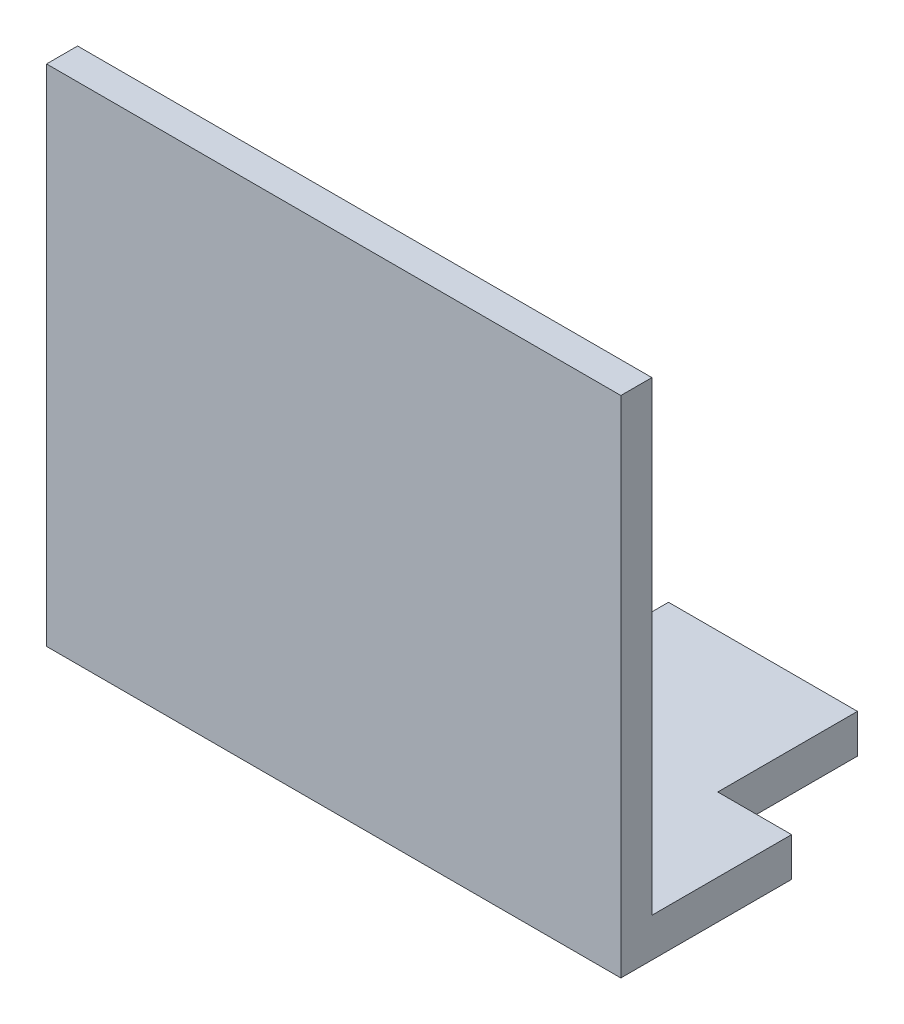
SolidWorks part; units mm, degrees
ref_plane "Спереди" through (0, 0, 0) normal (0, 0, 1) x (1, 0, 0)
ref_plane "Сверху" through (0, 0, 0) normal (0, 1, 0) x (1, 0, 0)
ref_plane "Справа" through (0, 0, 0) normal (1, 0, 0) x (0, 0, -1)
sketch "Эскиз1" plane through (0, 0, 0) normal (1, 0, 0) x (0, 0, -1)
  line L0 (0, 0) -> (0, 60)
  line L1 (0, 0) -> (36, 0)
  line L2 (36, 0) -> (36, -5)
  line L3 (36, -5) -> (-4, -5)
  line L4 (-4, -5) -> (-4, 60)
  line L5 (-4, 60) -> (0, 60)
extrude "Вытянуть1" add sketch "Эскиз1" against normal up to surface (74 mm away)
sketch "Эскиз2" plane through (0, 0, 0) normal (0, 1, 0) x (1, 0, 0)
  line L0 (-33.8574, 16) -> (-69.8554, 16)
  line L1 (-75.8574, 0) -> (-75.8574, 39.5929)
  line L2 (-75.8574, 39.5929) -> (-33.8574, 39.5929)
  line L3 (-33.8574, 39.5929) -> (-33.8574, 16)
  line L4 (-74, -4) -> (0, -4) construction
  line L5 (-69.8554, 16) -> (-69.8554, 0)
  line L6 (-74, 0) -> (0, 0) construction
  line L7 (-69.8554, 0) -> (-75.8574, 0)
  line L8 (0, 36) -> (0, 0) construction
  line L9 (-74, 36) -> (0, 36) construction
  line L10 (-9.513, 36) -> (0, 36)
  line L11 (0, 36) -> (0, 18)
  line L12 (-9.513, 36) -> (-9.513, 18)
  line L13 (-9.513, 18) -> (0, 18)
  dimension "D1" = 20
extrude "Вырез-Вытянуть1" cut sketch "Эскиз2" against normal through all
